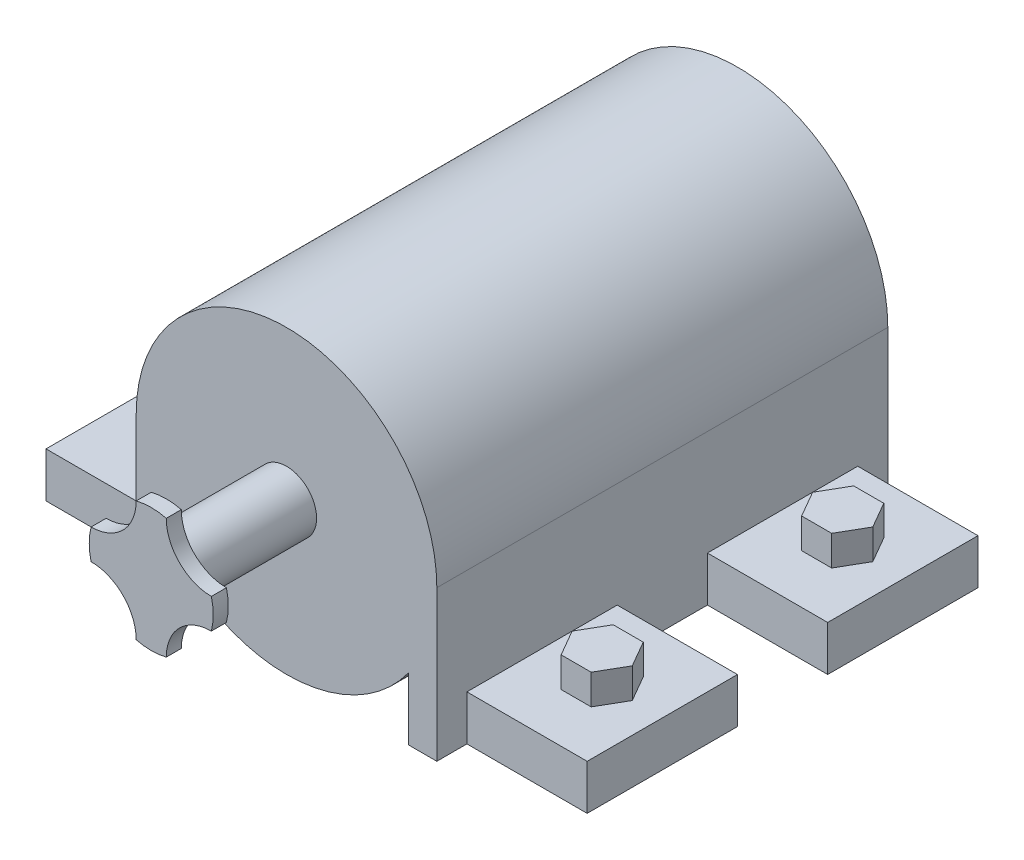
SolidWorks part; units mm, degrees
ref_plane "Płaszczyzna przednia" through (0, 0, 0) normal (0, 0, 1) x (1, 0, 0)
ref_plane "Płaszczyzna górna" through (0, 0, 0) normal (0, 1, 0) x (1, 0, 0)
ref_plane "Płaszczyzna prawa" through (0, 0, 0) normal (1, 0, 0) x (0, 0, -1)
sketch "Szkic1" plane through (0, 0, 0) normal (0, 0, 1) x (1, 0, 0)
  circle A0 centre (0, 0) radius 50
extrude "Dodanie-wyciągnięcie1" add sketch "Szkic1" along normal blind 150
sketch "Szkic2" plane through (0, 0, 150) normal (0, 0, 1) x (1, 0, 0)
  circle A0 centre (0, 0) radius 10
extrude "Dodanie-wyciągnięcie2" add sketch "Szkic2" along normal blind 40
sketch "Szkic3" plane through (0, 0, 190) normal (0, 0, 1) x (1, 0, 0)
  line L5 (-9.3934, -9.3934) -> (9.3934, 9.3934) construction
  line L6 (-9.3934, 9.3934) -> (9.3934, -9.3934) construction
  arc A0 (-5, -20) -> (-20, -5) centre (-20, -20) ccw
  arc A1 (20, -5) -> (5, -20) centre (20, -20) ccw
  arc A2 (5, 20) -> (20, 5) centre (20, 20) ccw
  arc A3 (-20, 5) -> (-5, 20) centre (-20, 20) ccw
  arc A4 (-20, 5) -> (-20, -5) centre (0, 0) ccw
  arc A5 (-5, -20) -> (5, -20) centre (0, 0) ccw
  arc A6 (20, -5) -> (20, 5) centre (0, 0) ccw
  arc A7 (5, 20) -> (-5, 20) centre (0, 0) ccw
  point P0 (0, 0)
  dimension "D1" = 40
  dimension "D2" = 40
extrude "Dodanie-wyciągnięcie3" add sketch "Szkic3" along normal blind 5
sketch "Szkic4" plane through (0, 0, 0) normal (0, 0, 1) x (1, 0, 0)
  line L0 (-50, 0) -> (-50, -50)
  line L1 (-50, -50) -> (-40.6104, -50)
  line L2 (-40.6104, -50) -> (-40.6104, -29.1684)
  line L3 (-40.6104, -29.1684) -> (-50, 0)
  circle A0 centre (0, 0) radius 50 construction
extrude "Dodanie-wyciągnięcie4" add sketch "Szkic4" along normal blind 150
sketch "Szkic5" plane through (-50, 0, 0) normal (-1, 0, 0) x (0, 0, 1)
  line L0 (150, -50) -> (0, -50) construction
  line L1 (10, -50) -> (60, -50)
  line L2 (10, -50) -> (10, -35)
  line L3 (10, -35) -> (60, -35)
  line L4 (60, -50) -> (60, -35)
  line L6 (90, -50) -> (140, -50)
  line L7 (90, -50) -> (90, -35)
  line L8 (90, -35) -> (140, -35)
  line L9 (140, -50) -> (140, -35)
  dimension "D1" = 10
  dimension "D2" = 10
  dimension "D3" = 50
  dimension "D4" = 50
  dimension "D5" = 15
  dimension "D6" = 15
extrude "Dodanie-wyciągnięcie5" add sketch "Szkic5" along normal blind 40
sketch "Szkic6" plane through (0, -35, 0) normal (0, 1, 0) x (1, 0, 0)
  line L0 (-90, -140) -> (-90, -90) construction
  line L1 (-65, -26.3397) -> (-75, -26.3397)
  line L2 (-75, -26.3397) -> (-80, -35)
  line L3 (-80, -35) -> (-75, -43.6603)
  line L4 (-75, -43.6603) -> (-65, -43.6603)
  line L5 (-65, -43.6603) -> (-60, -35)
  line L6 (-60, -35) -> (-65, -26.3397)
  line L7 (-60, -115) -> (-65, -106.3397)
  line L8 (-65, -106.3397) -> (-75, -106.3397)
  line L9 (-75, -106.3397) -> (-80, -115)
  line L10 (-80, -115) -> (-75, -123.6603)
  line L11 (-75, -123.6603) -> (-65, -123.6603)
  line L12 (-65, -123.6603) -> (-60, -115)
  line L13 (-90, -140) -> (-50, -140) construction
  line L14 (-90, -90) -> (-50, -90) construction
  line L15 (-90, -10) -> (-50, -10) construction
  line L16 (-90, -60) -> (-90, -10) construction
  circle A0 centre (-70, -35) radius 8.6603 construction
  circle A1 centre (-70, -115) radius 8.6603 construction
  point P20 (-68.1876, -157.1655)
  point P21 (-64.9089, -141.3397)
  dimension "D1" = 20
  dimension "D2" = 25
  dimension "D3" = 10
  dimension "D4" = 0
  dimension "D5" = 0
  dimension "D6" = 10
  dimension "D7" = 20
  dimension "D8" = 25
extrude "Dodanie-wyciągnięcie6" add sketch "Szkic6" along normal blind 10
mirror "Lustro1" about plane through (0, 0, 0) normal (1, 0, 0) of "Dodanie-wyciągnięcie4", "Dodanie-wyciągnięcie1", "Dodanie-wyciągnięcie5", "Dodanie-wyciągnięcie6"
